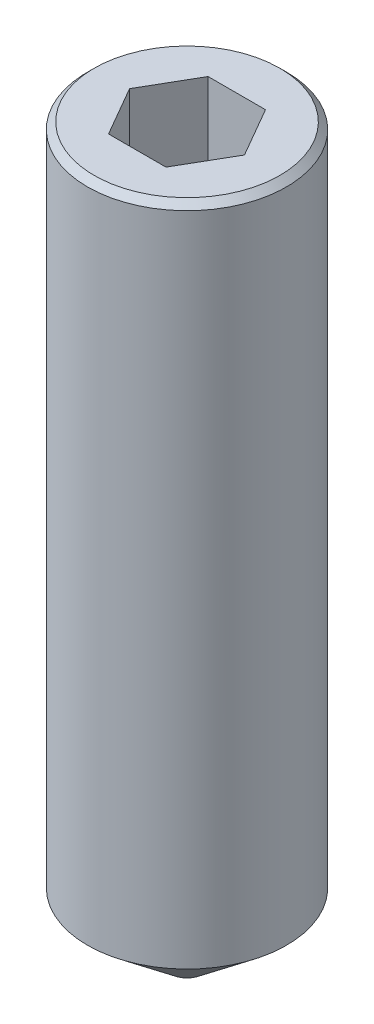
SolidWorks part; units mm, degrees
ref_plane "前视基准面" through (0, 0, 0) normal (0, 0, 1) x (1, 0, 0)
ref_plane "上视基准面" through (0, 0, 0) normal (0, 1, 0) x (1, 0, 0)
ref_plane "右视基准面" through (0, 0, 0) normal (1, 0, 0) x (0, 0, -1)
sketch "草图1" plane through (0, 0, 0) normal (0, 0, 1) x (1, 0, 0)
  line L0 (0, 0) -> (1.5, 0)
  line L1 (1.5, 0) -> (1.5, -10)
  line L2 (1.5, -10) -> (0.25, -11)
  line L3 (0, -11) -> (0, 0)
  line L4 (0, 8.7135) -> (0, -8.7135) construction
  line L5 (0.25, -11) -> (0, -11)
  point P10 (0, 0)
  dimension "D1" = 3
  dimension "D2" = 10
  dimension "D3" = 1
  dimension "D4" = 0.5
revolve "旋转1" add sketch "草图1" angle 360 about L4
sketch "草图2" plane through (0, 0, 0) normal (0, 1, 0) x (1, 0, 0)
  line L1 (-0.433, -0.75) -> (0.433, -0.75)
  line L2 (0.433, -0.75) -> (0.866, 0)
  line L3 (0.866, 0) -> (0.433, 0.75)
  line L4 (0.433, 0.75) -> (-0.433, 0.75)
  line L5 (-0.433, 0.75) -> (-0.866, 0)
  line L6 (-0.866, 0) -> (-0.433, -0.75)
  circle A0 centre (0, 0) radius 0.75 construction
  dimension "D1" = 1.5
extrude "切除-拉伸1" cut sketch "草图2" against normal blind 1.5
chamfer "倒角1" distance 0.1 angle 45 1 edges at (0, 0, 1.5)
